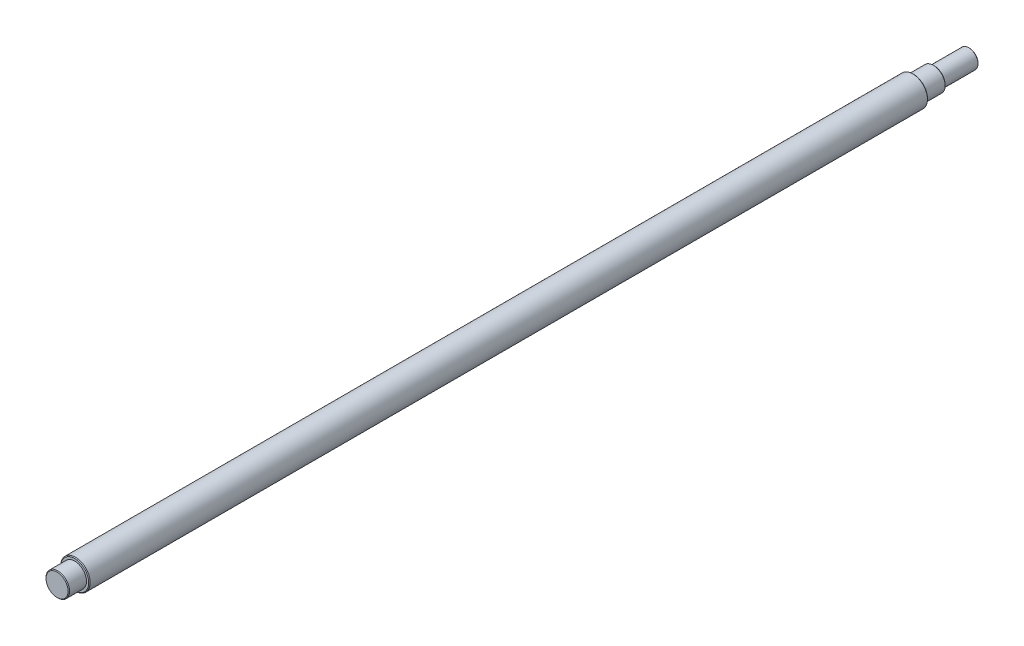
SolidWorks part; units mm, degrees
ref_plane "Front Plane" through (0, 0, 0) normal (0, 0, 1) x (1, 0, 0)
ref_plane "Top Plane" through (0, 0, 0) normal (0, 1, 0) x (1, 0, 0)
ref_plane "Right Plane" through (0, 0, 0) normal (1, 0, 0) x (0, 0, -1)
ref_plane "Plane1" through (0, 0, 304) normal (0, 0, 1) x (1, 0, 0)
sketch "Sketch1" plane through (0, 0, 304) normal (0, 0, 1) x (1, 0, 0)
  circle A0 centre (0, 0) radius 5
extrude "Boss-Extrude1" add sketch "Sketch1" against normal blind 285
sketch "Sketch2" plane through (0, 0, 19) normal (0, 0, -1) x (-1, 0, 0)
  circle A0 centre (0, 0) radius 4
extrude "Boss-Extrude2" add sketch "Sketch2" along normal blind 7
sketch "Sketch3" plane through (0, 0, 12) normal (0, 0, -1) x (-1, 0, 0)
  circle A0 centre (0, 0) radius 3.175
extrude "Boss-Extrude3" add sketch "Sketch3" along normal blind 12
sketch "Sketch4" plane through (0, 0, 304) normal (0, 0, 1) x (1, 0, 0)
  circle A0 centre (0, 0) radius 4
extrude "Boss-Extrude4" add sketch "Sketch4" along normal blind 6
chamfer "Chamfer1" distance 0.25 angle 45 5 edges at (-5, 0, 304) (-3.175, 0, 0) (-5, 0, 19) (4, 0, 310) (-4, 0, 12)
